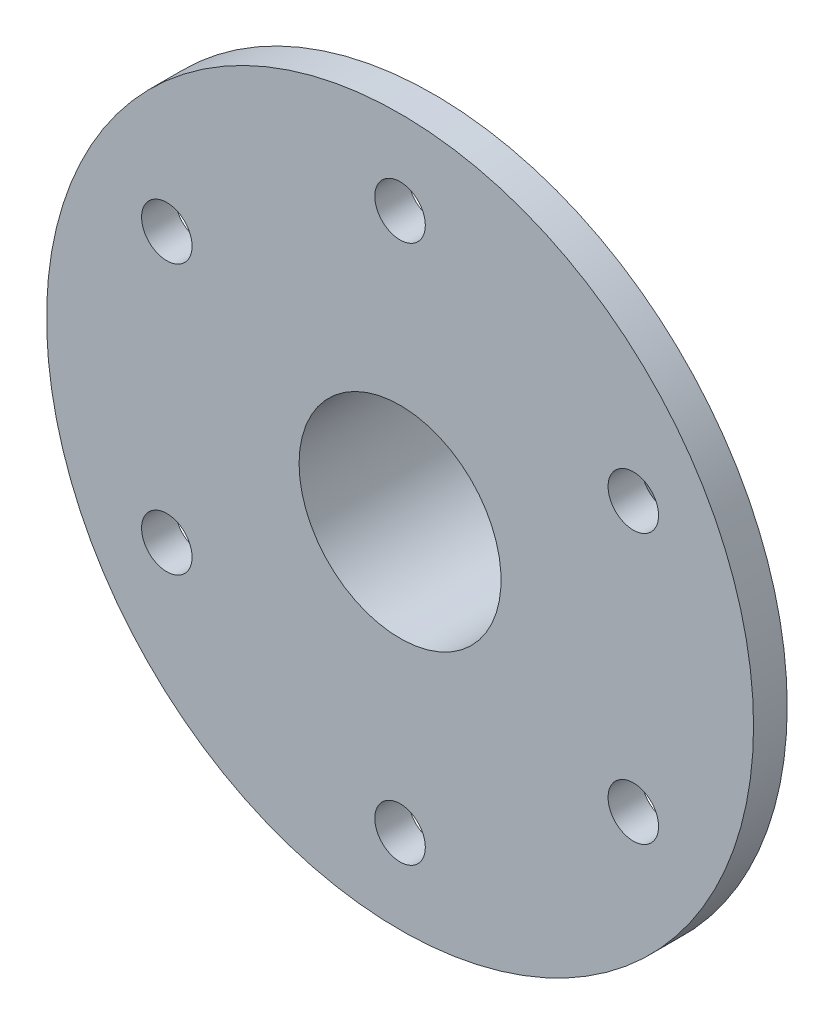
SolidWorks part; units mm, degrees
ref_plane "前视基准面" through (0, 0, 0) normal (0, 0, 1) x (1, 0, 0)
ref_plane "上视基准面" through (0, 0, 0) normal (0, 1, 0) x (1, 0, 0)
ref_plane "右视基准面" through (0, 0, 0) normal (1, 0, 0) x (0, 0, -1)
other "Configuration Table"
sketch "草图1" plane through (0, 0, 0) normal (0, 0, 1) x (1, 0, 0)
  circle A0 centre (0, 0) radius 9.985
  dimension "D1" = 19.97
extrude "凸台-拉伸1" add sketch "草图1" along normal blind 4
sketch "草图2" plane through (0, 0, 4) normal (0, 0, 1) x (1, 0, 0)
  circle A0 centre (0, 0) radius 11.5
  dimension "D1" = 23
extrude "凸台-拉伸2" add sketch "草图2" along normal blind 3
sketch "草图3" plane through (0, 0, 7) normal (0, 0, 1) x (1, 0, 0)
  circle A0 centre (0, 0) radius 21
  circle A1 centre (0, 16) radius 1.5
  circle A2 centre (13.8564, 8) radius 1.5
  circle A3 centre (13.8564, -8) radius 1.5
  circle A4 centre (0, -16) radius 1.5
  circle A5 centre (-13.8564, -8) radius 1.5
  circle A6 centre (-13.8564, 8) radius 1.5
  point P17 (0, 0)
  dimension "D1" = 42
  dimension "D2" = 3
  dimension "D3" = 16
extrude "凸台-拉伸3" add sketch "草图3" along normal blind 2
sketch "草图4" plane through (0, 0, 0) normal (0, 0, -1) x (-1, 0, 0)
  circle A0 centre (0, 0) radius 6
  dimension "D1" = 12
extrude "切除-拉伸1" cut sketch "草图4" against normal through all
fillet "圆角1" radius 1.5 1 edges at (11.5, 0, 7)
